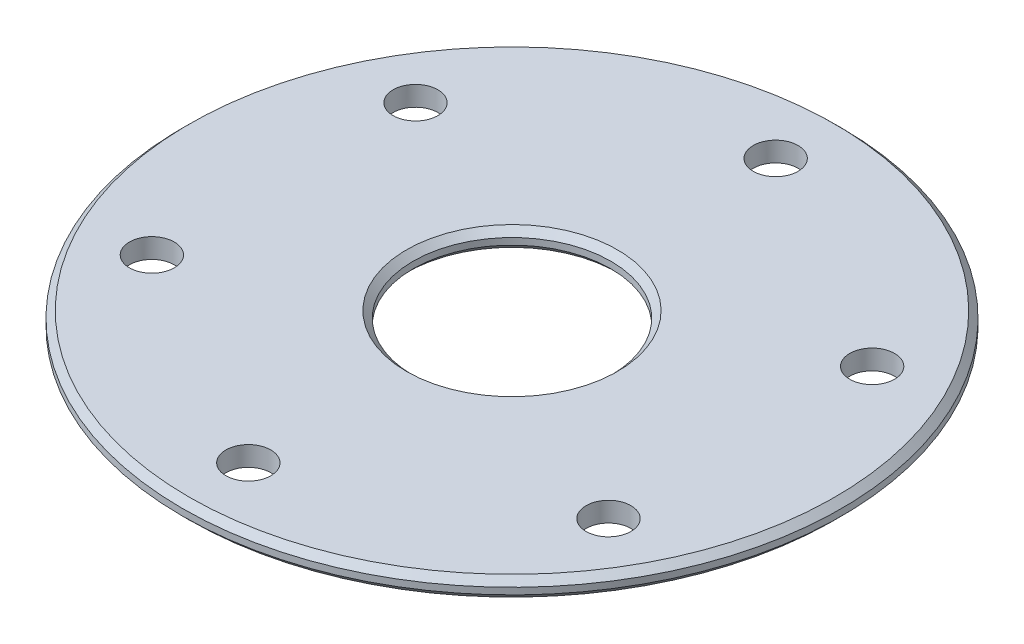
SolidWorks part; units mm, degrees
ref_plane "前视基准面" through (0, 0, 0) normal (0, 0, 1) x (1, 0, 0)
ref_plane "上视基准面" through (0, 0, 0) normal (0, 1, 0) x (1, 0, 0)
ref_plane "右视基准面" through (0, 0, 0) normal (1, 0, 0) x (0, 0, -1)
sketch "草图1" plane through (0, 0, 0) normal (0, 1, 0) x (1, 0, 0)
  line L0 (0, 0) -> (0, 58.2558)
  circle A0 centre (0, 0) radius 50
  circle A1 centre (0, 0) radius 40
  dimension "D1" = 100
  dimension "D2" = 80
extrude "凸台-拉伸1" add sketch "草图1" along normal blind 3
sketch "草图4" plane through (0, 0, 0) normal (0, -1, 0) x (1, 0, 0)
  line L0 (0, 0) -> (0, 48.5715)
  circle A0 centre (0, 0) radius 40
  dimension "D1" = 80
hole_wizard "M8 螺纹孔的螺纹孔钻头1" positions "草图5" profile "草图6" hole size "M8" standard "GB"
sketch "草图5" plane through (0, 0, 0) normal (0, -1, 0) x (-1, 0, 0)
  line L0 (0, 0) -> (0, -48.5715) construction
  circle A0 centre (0, 0) radius 40 construction
  point P0 (0, -40)
sketch "草图6" plane through (0, 0, 40) normal (1, 0, 0) x (0, 0, -1)
  line L0 (0, 0) -> (0, 18.0429)
  line L1 (0, 18.0429) -> (3.4, 16)
  line L2 (3.4, 16) -> (3.4, 0)
  line L5 (3.4, 0) -> (0, 0)
  line L10 (0, 18.0429) -> (-3.4, 16) construction
  line L11 (0, -6.35) -> (0, 107.95) construction
  dimension "孔直径" = 6.8
  dimension "孔深度" = 16
  dimension "导头角度" = 118
pattern_circular "阵列(圆周)1" count 6 over 360 about axis through (0, 0, 0) along (0, 1, 0) of "M8 螺纹孔的螺纹孔钻头1"
sketch "草图7" plane through (0, 0, 0) normal (0, -1, 0) x (1, 0, 0)
  circle A0 centre (0, 0) radius 15
  dimension "D1" = 30
extrude "切除-拉伸1" cut sketch "草图7" against normal blind 3
chamfer "倒角1" distance 1 angle 45 4 edges at (0, 3, -15) (0, 0, -15) (0, 3, 50) (0, 0, 50)
